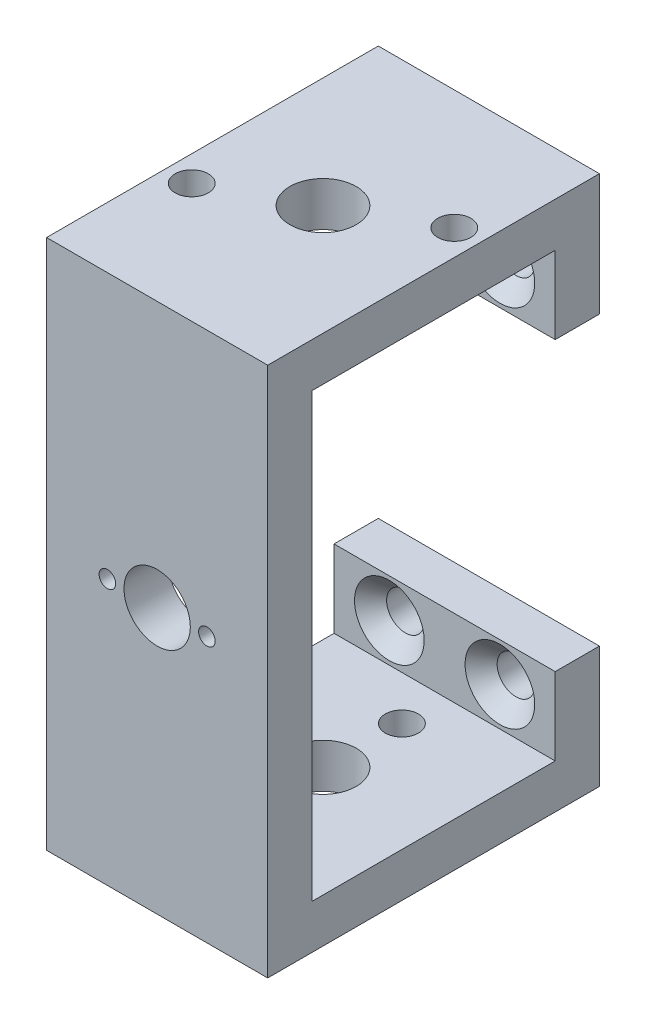
SolidWorks part; units mm, degrees
material "ABS"
ref_plane "Front Plane" through (0, 0, 0) normal (0, 0, 1) x (1, 0, 0)
ref_plane "Top Plane" through (0, 0, 0) normal (0, 1, 0) x (1, 0, 0)
ref_plane "Right Plane" through (0, 0, 0) normal (1, 0, 0) x (0, 0, -1)
sketch "Sketch1" plane through (0, 0, 0) normal (1, 0, 0) x (0, 0, -1)
  line L0 (-11, 0) -> (-15, 0) construction
  line L1 (-15, 0) -> (-15, 14)
  line L2 (-15, 14) -> (15, 14)
  line L3 (15, 14) -> (15, 0)
  line L4 (15, 0) -> (11, 0)
  line L5 (11, 0) -> (11, 10)
  line L6 (11, 10) -> (-11, 10)
  line L7 (-11, 10) -> (-11, 0)
  line L8 (-15, -10) -> (16.634, -10) construction
  line L9 (-15, 0) -> (-11, 0) construction
  line L10 (-15, 0) -> (-15, -20)
  line L12 (-11, 0) -> (-11, -30)
  line L13 (15, -20) -> (11, -20)
  line L14 (15, -34) -> (15, -20)
  line L15 (11, -20) -> (11, -30)
  line L17 (-15, -34) -> (15, -34)
  line L18 (-15, -20) -> (-15, -34)
  line L19 (11, -30) -> (-11, -30)
  point P0 (0, 10)
  point P24 (-15, -10)
  dimension "D1" = 14
  dimension "D2" = 4
  dimension "D3" = 4
  dimension "D4" = 30
  dimension "D5" = 20
extrude "Boss-Extrude1" add sketch "Sketch1" along normal blind 20
sketch "Sketch2" plane through (0, 0, 11) normal (0, 0, -1) x (-1, 0, 0)
  line L0 (0, -30) -> (0, 10) construction
  line L1 (-20, 10) -> (0, 10) construction
  circle A0 centre (-10, -10) radius 3
  point P5 (0, -10)
  point P9 (-10, 10)
  dimension "D1" = 6
extrude "Cut-Extrude1" cut sketch "Sketch2" against normal through all
sketch "Sketch3" plane through (0, 14, 0) normal (0, 1, 0) x (1, 0, 0)
  line L0 (20, 15) -> (0, 15) construction
  line L1 (0, 15) -> (0, -15) construction
  circle A0 centre (10, 0) radius 3
  point P5 (10, 15)
  point P9 (0, 0)
  dimension "D1" = 6
extrude "Cut-Extrude2" cut sketch "Sketch3" against normal through all
sketch "Sketch4" plane through (20, 0, 0) normal (1, 0, 0) x (0, 0, -1)
  line L0 (15, 0) -> (15, 14) construction
  line L1 (11, 0) -> (15, 0)
  line L2 (11, 0) -> (11, 3)
  line L3 (11, 3) -> (15, 3)
  line L4 (15, 0) -> (15, 3)
  line L5 (15, -34) -> (15, -20) construction
  line L6 (11, -20) -> (15, -20)
  line L7 (11, -20) -> (11, -23)
  line L8 (11, -23) -> (15, -23)
  line L9 (15, -20) -> (15, -23)
  dimension "D1" = 3
extrude "Cut-Extrude3" cut sketch "Sketch4" against normal through all
sketch "Sketch5" plane through (0, -34, 0) normal (0, -1, 0) x (1, 0, 0)
  circle A0 centre (9.8646, 6.9987) radius 1.5
  circle A1 centre (10.1354, -6.9987) radius 1.5
  dimension "D1" = 3
extrude "Cut-Extrude4" cut sketch "Sketch5" against normal up to next
sketch "Sketch6" plane through (0, 14, 0) normal (0, 1, 0) x (1, 0, 0)
  circle A0 centre (17.6796, 4.1936) radius 1.5
  circle A1 centre (2.3204, -4.1936) radius 1.5
  dimension "D1" = 3
  dimension "D2" = 3
extrude "Cut-Extrude5" cut sketch "Sketch6" against normal up to next
sketch "Sketch7" plane through (0, 0, -15) normal (0, 0, -1) x (-1, 0, 0)
  line L0 (-15, 6.5) -> (-5, 6.5) construction
  line L1 (0, 3) -> (-20, 3) construction
  circle A0 centre (-15, 6.5) radius 1.5
  circle A1 centre (-5, 6.5) radius 1.5
  point P4 (-10, 6.5)
  point P7 (-10, 3)
  dimension "D1" = 3
  dimension "D2" = 3
  dimension "D3" = 3.5
  dimension "D4" = 10
extrude "Cut-Extrude6" cut sketch "Sketch7" against normal up to next
ref_plane "Plane1" through (0, -10, 0) normal (0, 1, 0) x (1, 0, 0)
hole_wizard "CSK for M3 Flat Head Machine Screw1" positions "3DSketch1" profile "Sketch8" countersink size "M3" standard "ANSI Metric"
sketch3d "3DSketch1"
  line L0 (5, 6.5, -11) -> (5, 6.5, -15) construction
  line L1 (15, 6.5, -11) -> (15, 6.5, -15) construction
  point P0 (5, 6.5, -11)
  point P2 (15, 6.5, -11)
sketch "Sketch8" plane through (5, 6.5, -11) normal (1, 0, 0) x (0, -1, 0)
  line L0 (0, 0) -> (0, 4)
  line L1 (0, 4) -> (1.7, 4)
  line L2 (1.7, 4) -> (1.7, 1.45)
  line L3 (1.7, 1.45) -> (3.15, 0)
  line L5 (3.15, 0) -> (0, 0)
  line L6 (-1.7, 1.45) -> (-3.15, 0) construction
  line L11 (0, -6.35) -> (0, 107.95) construction
  dimension "Thru Hole Dia." = 3.4
  dimension "Thru Hole Depth" = 4
  dimension "Near C'Sink Dia." = 6.3
  dimension "Near C'Sink Angle" = 90
mirror "Mirror1" about plane through (0, -10, 0) normal (0, 1, 0) of "CSK for M3 Flat Head Machine Screw1", "Cut-Extrude6"
sketch "Sketch9" plane through (0, 0, 15) normal (0, 0, 1) x (1, 0, 0)
  circle A0 centre (5.5, -10) radius 0.75
  circle A1 centre (14.5, -10) radius 0.75
  dimension "D1" = 1.5
  dimension "D2" = 1.5
extrude "Cut-Extrude7" cut sketch "Sketch9" against normal through all
